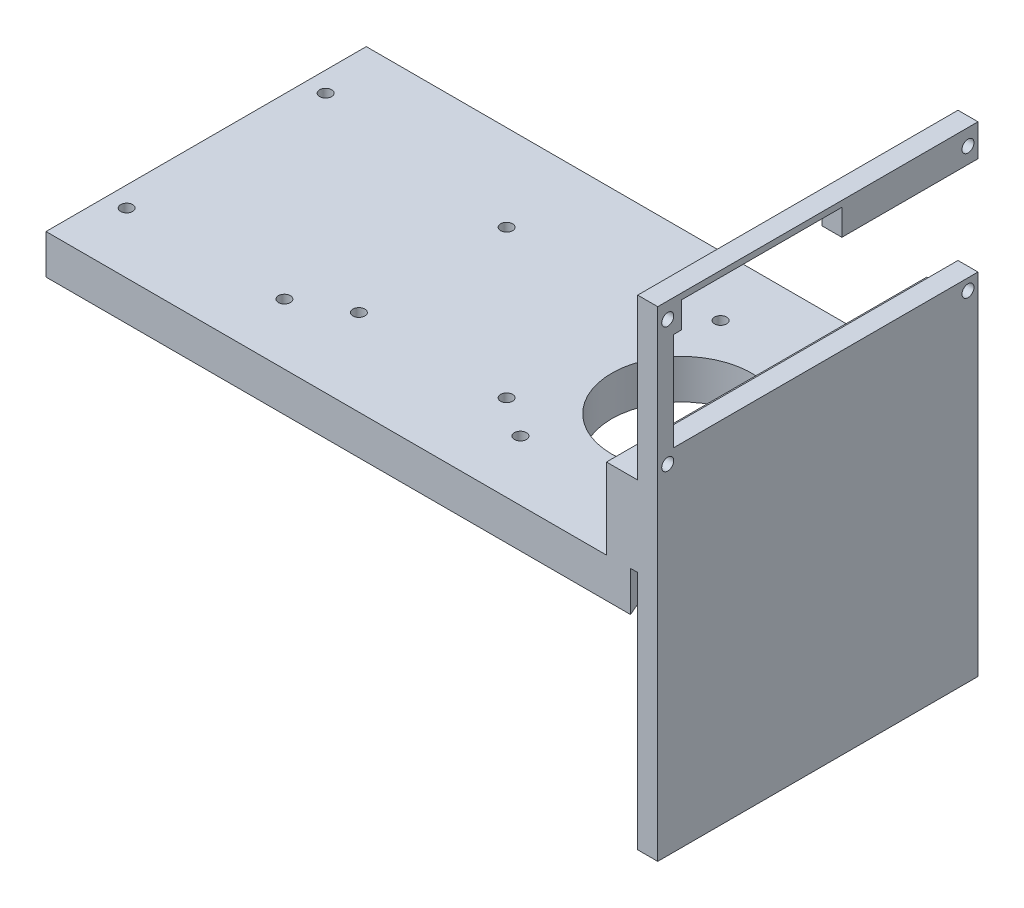
SolidWorks part; units mm, degrees
ref_plane "Front Plane" through (0, 0, 0) normal (0, 0, 1) x (1, 0, 0)
ref_plane "Top Plane" through (0, 0, 0) normal (0, 1, 0) x (1, 0, 0)
ref_plane "Right Plane" through (0, 0, 0) normal (1, 0, 0) x (0, 0, -1)
sketch "Sketch1" plane through (0, 0, 0) normal (0, 0, 1) x (1, 0, 0)
  line L0 (0, 0) -> (0, 30)
  line L1 (0, 30) -> (12.8, 30)
  line L2 (12.8, 30) -> (12.8, 0)
  line L3 (12.8, 0) -> (7.8, 0)
  line L4 (7.8, 0) -> (7.8, 10)
  line L5 (7.8, 10) -> (6, 10)
  line L6 (6, 10) -> (6, 0)
  line L7 (6, 0) -> (0, 0)
  dimension "D1" = 1.8
  dimension "D2" = 6
  dimension "D3" = 5
  dimension "D4" = 30
  dimension "D5" = 10
extrude "Boss-Extrude1" add sketch "Sketch1" along normal blind 80
sketch "Sketch3" plane through (0, 0, 0) normal (0, -1, 0) x (1, 0, 0)
  line L0 (7.8, 80) -> (12.8, 80)
  line L1 (12.8, 80) -> (12.8, 0)
  line L2 (12.8, 0) -> (7.8, 0)
  line L3 (7.8, 0) -> (7.8, 80)
sketch "Esboço2" plane through (0, 0, 0) normal (0, -1, 0) x (1, 0, 0)
  line L0 (6, 80) -> (6, 0)
  arc A0 (6, 80) -> (6, 0) centre (93.9293, 40) ccw
  dimension "D1" = 96.6
extrude "Corte-extrusão1" cut sketch "Esboço2" against normal blind 10
extrude "Boss-Extrude2" add sketch "Sketch3" along normal blind 50
sketch "Sketch4" plane through (0, 0, 0) normal (-1, 0, 0) x (0, 0, 1)
  line L0 (80, 30) -> (80, 0) construction
  line L1 (80, 9.8625) -> (0, 9.8625)
  line L2 (80, 9.8625) -> (80, 0)
  line L3 (80, 0) -> (0, 0)
  line L4 (0, 9.8625) -> (0, 0)
extrude "Boss-Extrude3" add sketch "Sketch4" along normal blind 140
sketch "Sketch5" plane through (0, 9.8625, 0) normal (0, 1, 0) x (1, 0, 0)
  line L0 (-140, -80) -> (0, -80) construction
  line L1 (0, -80) -> (0, -62.5577) construction
  line L2 (-140, 0) -> (0, 0) construction
  line L3 (-140, -80) -> (-140, 0) construction
  circle A0 centre (-6.5, -65) radius 1.5
  circle A1 centre (-36.5, -65) radius 1.5
  circle A2 centre (-6.5, -15) radius 1.5
  circle A3 centre (-36.5, -15) radius 1.5
  circle A4 centre (-21.2005, -40) radius 17.5
  circle A5 centre (-46.5, -21.55) radius 1.5
  circle A6 centre (-46.5, -58.45) radius 1.5
  circle A7 centre (-83.4, -21.55) radius 1.5
  circle A8 centre (-83.4, -58.45) radius 1.5
  circle A9 centre (-95.6, -64.85) radius 1.5
  circle A10 centre (-135, -64.85) radius 1.5
  circle A11 centre (-135, -15.15) radius 1.5
  point P26 (0, 0)
  point P31 (0, 0)
  point P32 (0, 0)
  dimension "D1" = 3
  dimension "D6" = 35
  dimension "D9" = 3
  dimension "D14" = 3
  dimension "D2" = 50
  dimension "D3" = 30
  dimension "D4" = 15
  dimension "D5" = 6.5
  dimension "D7" = 29.31
  dimension "D8" = 29.31
  dimension "D10" = 36.9
  dimension "D11" = 36.9
  dimension "D12" = 21.55
  dimension "D13" = 10
  dimension "D15" = 39.4
  dimension "D16" = 49.7
  dimension "D17" = 5
  dimension "D18" = 15.15
extrude "Cut-Extrude1" cut sketch "Sketch5" against normal blind 40
sketch "Sketch6" plane through (0, 30, 0) normal (0, 1, 0) x (1, 0, 0)
  line L0 (12.8, -80) -> (0, -80) construction
  line L1 (12.8, 0) -> (7.8, 0)
  line L2 (12.8, 0) -> (12.8, -80)
  line L3 (12.8, -80) -> (7.8, -80)
  line L4 (7.8, 0) -> (7.8, -80)
  dimension "D1" = 5
extrude "Boss-Extrude4" add sketch "Sketch6" along normal blind 40
sketch "Sketch7" plane through (12.8, 0, 0) normal (1, 0, 0) x (0, 0, -1)
  line L0 (-74, 68.5) -> (-74, 62)
  line L1 (-74, 62) -> (-76, 62)
  line L2 (-76, 62) -> (-76, 37.5)
  line L3 (-76, 37.5) -> (0, 37.5)
  line L4 (0, 37.5) -> (0, 62)
  line L5 (0, 62) -> (-34, 62)
  line L6 (-34, 62) -> (-34, 68.5)
  line L7 (-34, 68.5) -> (-74, 68.5)
  line L8 (-80, -50) -> (-80, 70) construction
  line L9 (-80, 70) -> (0, 70) construction
  line L10 (-85.9777, 68.5) -> (4.9186, 68.5) construction
  line L11 (-85.9777, 32.2) -> (4.9186, 32.2) construction
  line L12 (0, -50) -> (0, 70) construction
  circle A0 centre (-77.5, 66) radius 1.5
  circle A1 centre (-2.5, 66) radius 1.5
  circle A2 centre (-2.5, 34.7) radius 1.5
  circle A3 centre (-77.5, 34.7) radius 1.5
  point P24 (0, 0)
  point P25 (0, 0)
  point P26 (0, 0)
  point P27 (0, 0)
  dimension "D9" = 3
  dimension "D1" = 76
  dimension "D2" = 4
  dimension "D3" = 6.5
  dimension "D4" = 24.5
  dimension "D5" = 8
  dimension "D6" = 40
  dimension "D7" = 2
  dimension "D8" = 5.3
  dimension "D10" = 2.5
  dimension "D11" = 2.5
  dimension "D12" = 2.5
  dimension "D13" = 2.5
extrude "Cut-Extrude2" cut sketch "Sketch7" against normal blind 40
